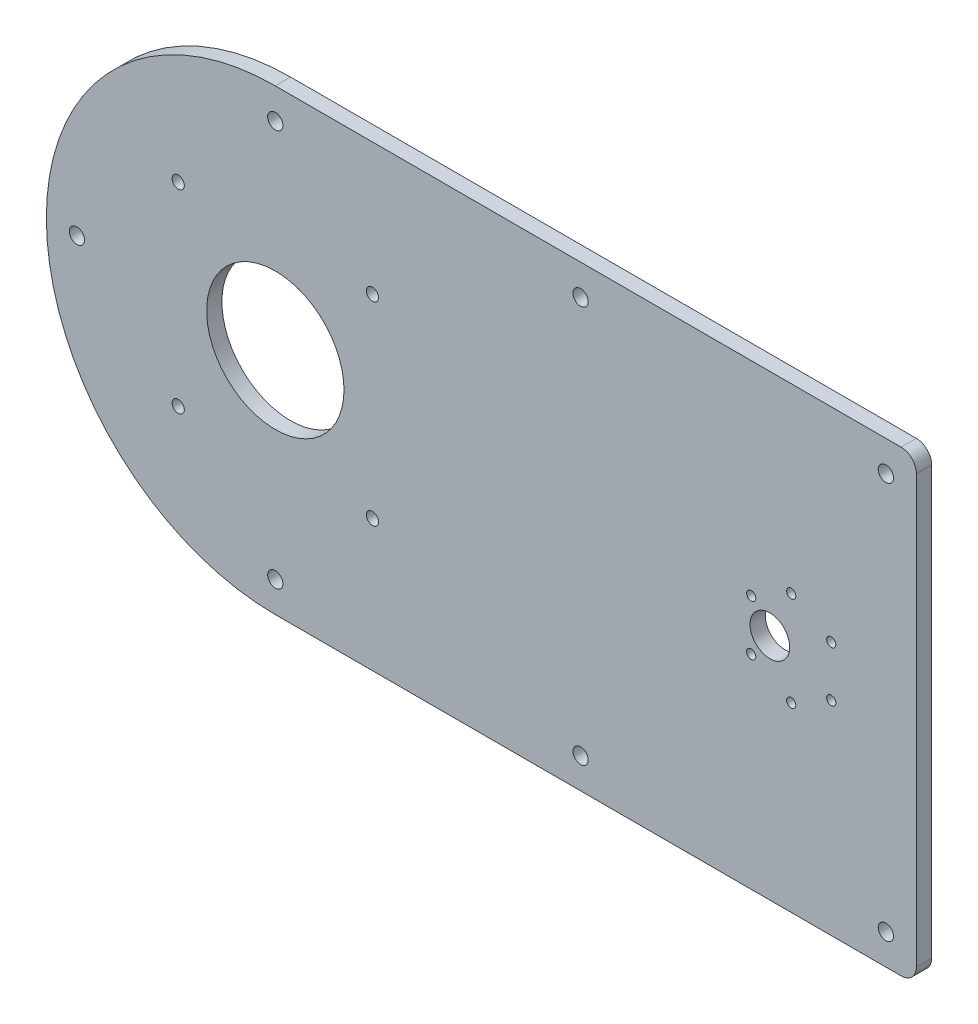
SolidWorks part; units mm, degrees
ref_plane "Front Plane" through (0, 0, 0) normal (0, 0, 1) x (1, 0, 0)
ref_plane "Top Plane" through (0, 0, 0) normal (0, 1, 0) x (1, 0, 0)
ref_plane "Right Plane" through (0, 0, 0) normal (1, 0, 0) x (0, 0, -1)
sketch "Sketch1" plane through (0, 0, 0) normal (0, 0, 1) x (1, 0, 0)
  line L1 (30.0007, 92.5455) -> (235.0007, 92.5455)
  line L3 (30.0007, -57.4545) -> (235.0007, -57.4545)
  line L4 (240.0007, 87.5455) -> (240.0007, -52.4545)
  arc A0 (235.0007, -57.4545) -> (240.0007, -52.4545) centre (235.0007, -52.4545) ccw
  arc A1 (235.0007, 92.5455) -> (240.0007, 87.5455) centre (235.0007, 87.5455) cw
  arc A2 (30.0007, 92.5455) -> (30.0007, -57.4545) centre (30.0007, 17.5455) ccw
  circle A7 centre (-34.9993, 17.5455) radius 2.5
  circle A10 centre (30.0007, -47.4545) radius 2.5
  circle A11 centre (30.0007, 82.5455) radius 2.5
  circle A12 centre (230.0007, -47.4545) radius 2.5
  circle A13 centre (230.0007, 82.5455) radius 2.5
  circle A15 centre (130.0007, 82.5455) radius 2.5
  circle A16 centre (130.0007, -47.4545) radius 2.5
  circle A18 centre (30.0007, 17.5455) radius 22.5
  circle A23 centre (61.8157, 49.3605) radius 2
  circle A24 centre (61.8157, -14.2695) radius 2
  circle A25 centre (-1.8143, -14.2695) radius 2
  circle A26 centre (-1.8143, 49.3605) radius 2
  circle A27 centre (192.0007, 17.5455) radius 6.5
  circle A31 centre (199.0007, 33.0455) radius 1.5
  circle A32 centre (199.0007, 2.0455) radius 1.5
  circle A33 centre (185.8934, 25.8189) radius 1.5
  circle A34 centre (212.108, 25.8189) radius 1.5
  circle A35 centre (212.108, 9.2721) radius 1.5
  circle A36 centre (185.8934, 9.2721) radius 1.5
  point P2 (30.0007, 17.5455)
  point P12 (192.0007, 17.5455)
  point P14 (30.0007, 17.5455)
  point P21 (-34.9993, 17.5455)
  point P23 (30.0007, 17.5455)
  point P53 (30.0007, 17.5455)
  point P54 (30.0007, 17.5455)
  dimension "D1" = 5
  dimension "D2" = 13
  dimension "D3" = 45
  dimension "D4" = 5
  dimension "D5" = 5
  dimension "D6" = 5
  dimension "D7" = 5
  dimension "D8" = 5
  dimension "D9" = 5
  dimension "D10" = 5
  dimension "D11" = 4
  dimension "D12" = 4
  dimension "D13" = 4
  dimension "D14" = 4
  dimension "D15" = 3
  dimension "D16" = 3
  dimension "D17" = 3
  dimension "D18" = 3
  dimension "D19" = 3
  dimension "D20" = 3
  dimension "D21" = 162
extrude "Boss-Extrude1" add sketch "Sketch1" along normal blind 5
